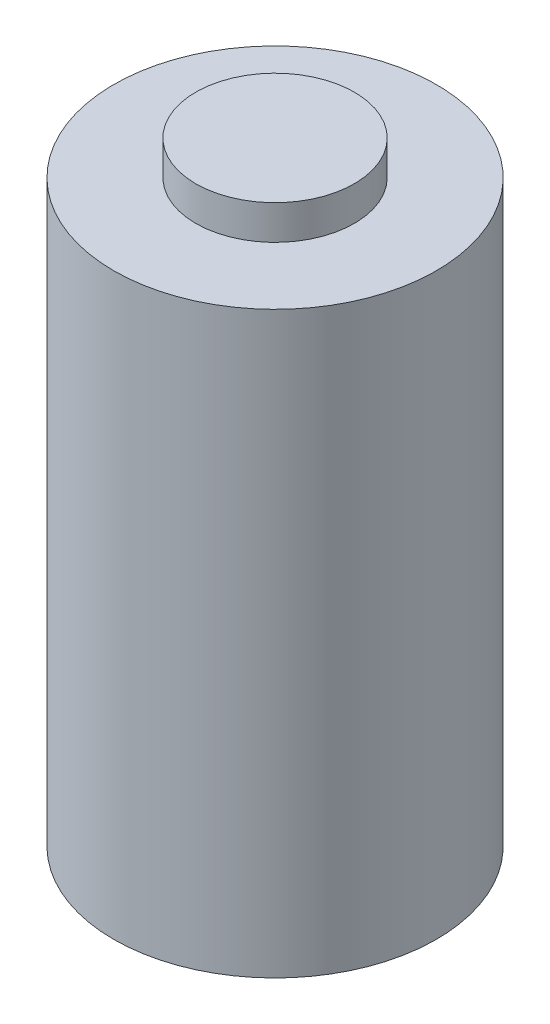
SolidWorks part; units mm, degrees
material "2006"
ref_plane "前视基准面" through (0, 0, 0) normal (0, 0, 1) x (1, 0, 0)
ref_plane "上视基准面" through (0, 0, 0) normal (0, 1, 0) x (1, 0, 0)
ref_plane "右视基准面" through (0, 0, 0) normal (1, 0, 0) x (0, 0, -1)
other "Configuration Table"
sketch "草图1" plane through (0, 0, 0) normal (0, 1, 0) x (1, 0, 0)
  circle A0 centre (0, 0) radius 12.2
  dimension "D1" = 24.4
extrude "凸台-拉伸1" add sketch "草图1" along normal blind 43.8
sketch "草图2" plane through (0, 43.8, 0) normal (0, 1, 0) x (1, 0, 0)
  circle A0 centre (0, 0) radius 6
extrude "凸台-拉伸2" add sketch "草图2" along normal blind 2.6
